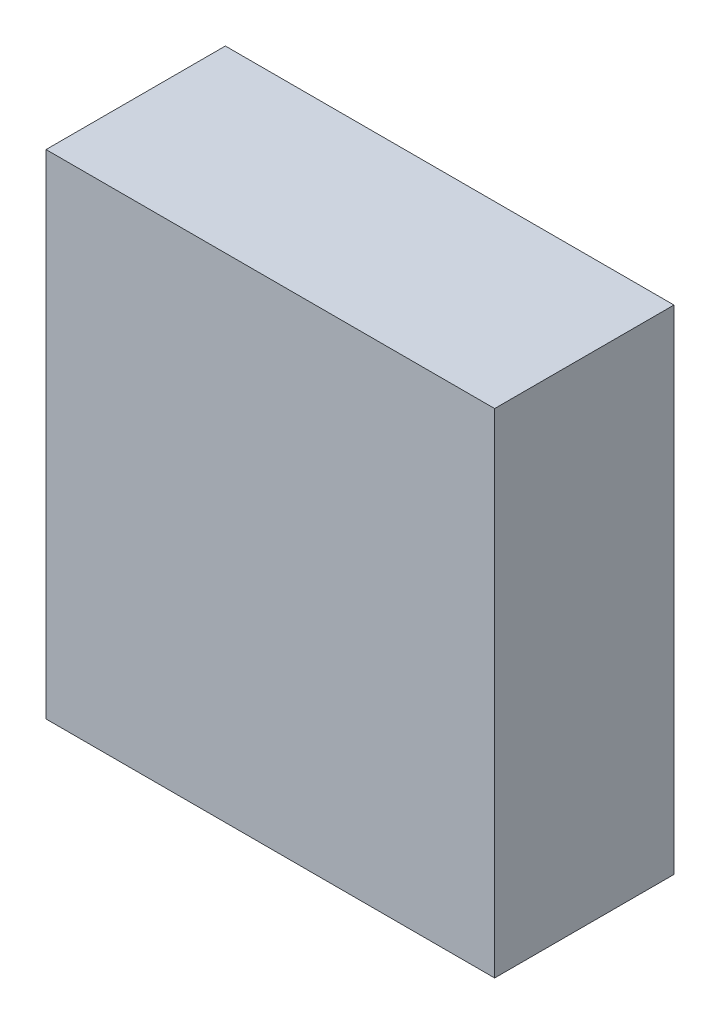
SolidWorks part; units mm, degrees
ref_plane "Front Plane" through (0, 0, 0) normal (0, 0, 1) x (1, 0, 0)
ref_plane "Top Plane" through (0, 0, 0) normal (0, 1, 0) x (1, 0, 0)
ref_plane "Right Plane" through (0, 0, 0) normal (1, 0, 0) x (0, 0, -1)
sketch "Sketch1" plane through (0, 0, 0) normal (0, 0, 1) x (1, 0, 0)
  line L0 (-1.3016, 1.55) -> (1.2, 1.55)
  line L1 (1.2, 1.55) -> (1.2, -1.2)
  line L2 (1.2, -1.2) -> (-1.3016, -1.2)
  line L3 (-1.3016, -1.2) -> (-1.3016, 1.55)
extrude "Component_Outline" add sketch "Sketch1" along normal blind 1 separate body
sketch3d "3DSketch1"
  line L0 (0, 0, 0) -> (1, 0, 0)
  line L1 (0, 0, 0) -> (0, 1, 0)
  line L2 (0, 0, 0) -> (0, 0, 1)
  point P0 (0, 0, 0)
